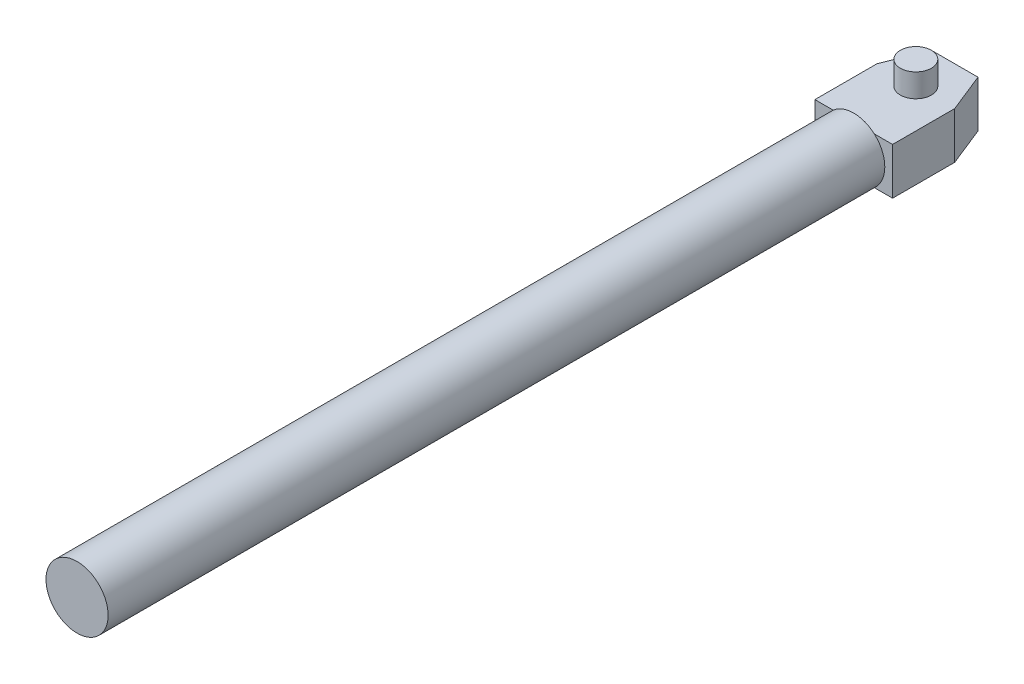
SolidWorks part; units mm, degrees
ref_plane "Front Plane" through (0, 0, 0) normal (0, 0, 1) x (1, 0, 0)
ref_plane "Top Plane" through (0, 0, 0) normal (0, 1, 0) x (1, 0, 0)
ref_plane "Right Plane" through (0, 0, 0) normal (1, 0, 0) x (0, 0, -1)
sketch "Sketch1" plane through (0, 0, 0) normal (0, 0, 1) x (1, 0, 0)
  circle A0 centre (0, 0) radius 20
  dimension "D1" = 40
extrude "Boss-Extrude1" add sketch "Sketch1" along normal blind 500
sketch "Sketch2" plane through (0, 0, 0) normal (0, 1, 0) x (1, 0, 0)
  line L0 (-25, 40) -> (-15, 65)
  line L1 (-25, 0) -> (25, 0)
  line L2 (-25, 0) -> (-25, 40)
  line L3 (-15, 65) -> (15, 65)
  line L4 (25, 0) -> (25, 40)
  line L5 (15, 65) -> (25, 40)
  point P1 (25, 65)
  point P2 (-25, 65)
  dimension "D1" = 25
  dimension "D2" = 10
  dimension "D3" = 10
  dimension "D4" = 25
  dimension "D5" = 50
  dimension "D6" = 65
extrude "Boss-Extrude2" add sketch "Sketch2" along normal mid plane 30
sketch "Sketch4" plane through (0, 0, 0) normal (0, 1, 0) x (1, 0, 0)
  line L0 (13.2288, 0) -> (-13.2288, 0) construction
  circle A0 centre (0, 40) radius 10
  dimension "D1" = 20
  dimension "D2" = 40
extrude "Boss-Extrude3" add sketch "Sketch4" along normal mid plane 60
